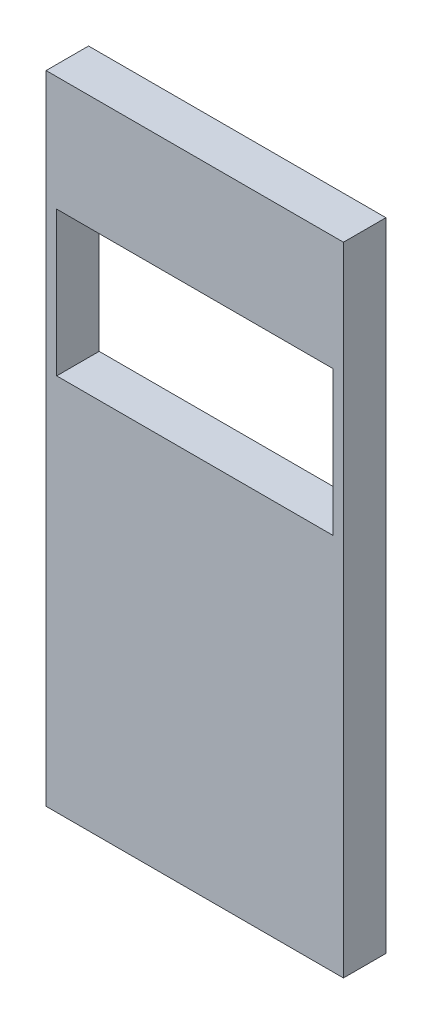
SolidWorks part; units mm, degrees
ref_plane "Front Plane" through (0, 0, 0) normal (0, 0, 1) x (1, 0, 0)
ref_plane "Top Plane" through (0, 0, 0) normal (0, 1, 0) x (1, 0, 0)
ref_plane "Right Plane" through (0, 0, 0) normal (1, 0, 0) x (0, 0, -1)
sketch "Sketch1" plane through (0, 0, 0) normal (0, 0, 1) x (1, 0, 0)
  line L1 (35, -75) -> (-35, -75)
  line L2 (35, -75) -> (35, 75)
  line L3 (35, 75) -> (-35, 75)
  line L4 (-35, -75) -> (-35, 75)
  line L5 (35, -75) -> (-35, 75) construction
  line L6 (35, 75) -> (-35, -75) construction
  point P0 (0, 0)
  dimension "D1" = 150
  dimension "D2" = 70
extrude "Boss-Extrude1" add sketch "Sketch1" along normal blind 10
sketch "Sketch3" plane through (0, 0, 0) normal (0, 0, -1) x (-1, 0, 0)
  line L1 (32.5, 14) -> (-32.5, 14)
  line L2 (32.5, 14) -> (32.5, 48)
  line L3 (32.5, 48) -> (-32.5, 48)
  line L4 (-32.5, 14) -> (-32.5, 48)
  line L5 (32.5, 14) -> (-32.5, 48) construction
  line L6 (32.5, 48) -> (-32.5, 14) construction
  line L7 (-35, 75) -> (35, 75) construction
  point P0 (0, 31)
  dimension "D1" = 44
  dimension "D2" = 34
  dimension "D3" = 65
extrude "Cut-Extrude1" cut sketch "Sketch3" against normal through all contours L3 L4 L1 L2
